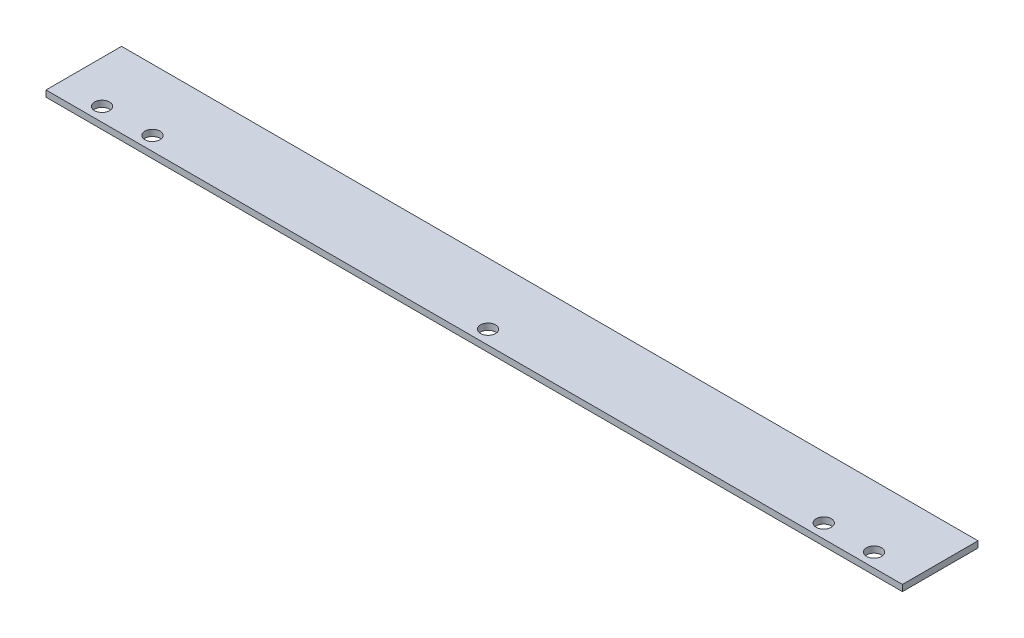
SolidWorks part; units mm, degrees
ref_plane "Front Plane" through (0, 0, 0) normal (0, 0, 1) x (1, 0, 0)
ref_plane "Top Plane" through (0, 0, 0) normal (0, 1, 0) x (1, 0, 0)
ref_plane "Right Plane" through (0, 0, 0) normal (1, 0, 0) x (0, 0, -1)
sketch "Sketch2" plane through (0, 0, 0) normal (0, 1, 0) x (1, 0, 0)
  line L0 (-107.95, -9.525) -> (-107.95, -2.5449) construction
  line L1 (-107.95, -9.525) -> (107.95, -9.525)
  line L2 (-107.95, -9.525) -> (-107.95, 9.525)
  line L3 (-107.95, 9.525) -> (107.95, 9.525)
  line L4 (107.95, -9.525) -> (107.95, 9.525)
  line L5 (-107.95, -9.525) -> (107.95, 9.525) construction
  line L6 (-107.95, 9.525) -> (107.95, -9.525) construction
  point P0 (0, 0)
  dimension "D1" = 19.05
extrude "Boss-Extrude1" add sketch "Sketch2" along normal blind 1.5875
hole_wizard "#6 Clearance Hole1" positions "Sketch3" profile "Sketch4" hole size "#6" standard "ANSI Inch" end condition up to next
sketch "Sketch3" plane through (0, 1.5875, 0) normal (0, 1, 0) x (1, 0, 0)
  line L5 (-97.3122, -7.7494) -> (-97.3122, -4.3204) construction
  line L7 (97.3122, -7.7494) -> (97.3122, -4.3204) construction
  arc A0 (-97.3122, -4.3204) -> (-97.3122, -7.7494) centre (-97.3452, -6.0349) ccw construction
  arc A1 (97.3122, -7.7494) -> (97.3122, -4.3204) centre (97.3452, -6.0349) ccw construction
  point P0 (-97.3122, -6.0349)
  point P2 (0, -6.0349)
  point P4 (97.3122, -6.0349)
  point P35 (97.3122, -6.0349)
  point P37 (-97.3122, -6.0349)
  point P38 (-84.6122, -6.0349)
  point P40 (84.6122, -6.0349)
  dimension "D1" = 12.7
  dimension "D2" = 12.7
sketch "Sketch4" plane through (-97.3122, 1.5875, 6.0349) normal (1, 0, 0) x (0, 0, 1)
  line L0 (0, 0) -> (0, 1.5875)
  line L1 (0, 1.5875) -> (1.8986, 1.5875)
  line L2 (1.8986, 1.5875) -> (1.8986, 0)
  line L5 (1.8986, 0) -> (0, 0)
  line L11 (0, -6.35) -> (0, 107.95) construction
  dimension "Thru Hole Dia." = 3.7973
  dimension "Thru Hole Depth" = 1.5875
